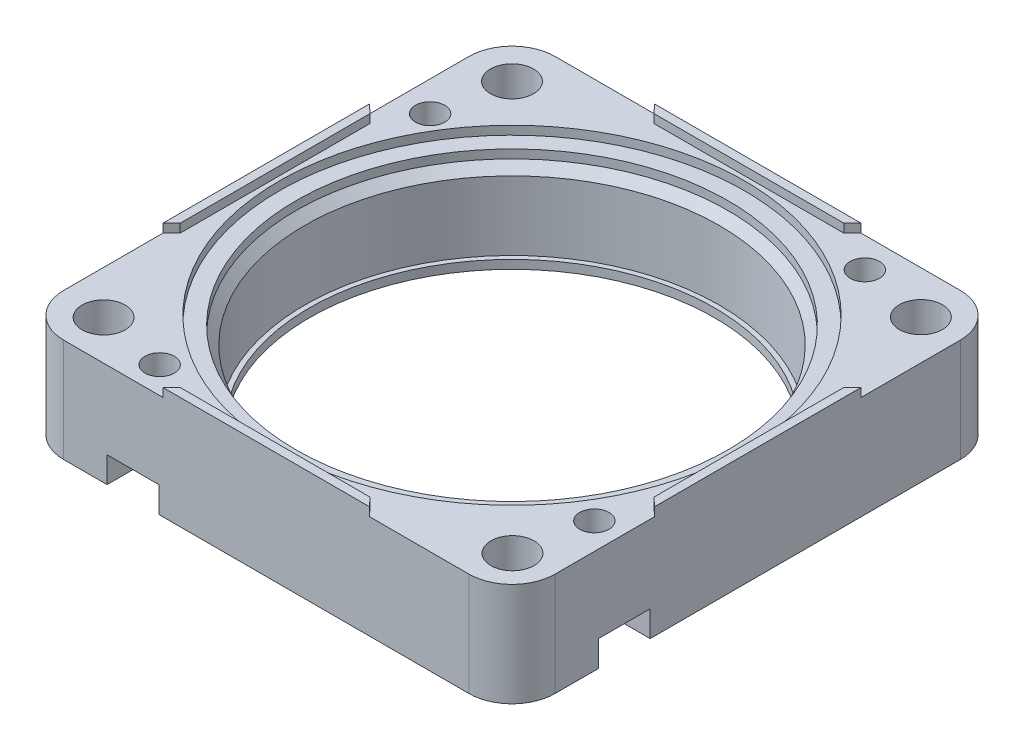
SolidWorks part; units mm, degrees
ref_plane "Front Plane" through (0, 0, 0) normal (0, 0, 1) x (1, 0, 0)
ref_plane "Top Plane" through (0, 0, 0) normal (0, 1, 0) x (1, 0, 0)
ref_plane "Right Plane" through (0, 0, 0) normal (1, 0, 0) x (0, 0, -1)
sketch "Sketch1" plane through (0, 0, 0) normal (0, 1, 0) x (1, 0, 0)
  line L1 (28.5, -28.5) -> (-28.5, -28.5)
  line L2 (28.5, -28.5) -> (28.5, 28.5)
  line L3 (28.5, 28.5) -> (-28.5, 28.5)
  line L4 (-28.5, -28.5) -> (-28.5, 28.5)
  line L5 (28.5, -28.5) -> (-28.5, 28.5) construction
  line L6 (28.5, 28.5) -> (-28.5, -28.5) construction
  point P0 (0, 0)
  dimension "D1" = 57
extrude "Boss-Extrude1" add sketch "Sketch1" along normal blind 12
fillet "Fillet1" radius 5 4 edges at (-28.5, 6, 28.5) (-28.5, 6, -28.5) (28.5, 6, -28.5) (28.5, 6, 28.5)
sketch "Sketch2" plane through (0, 12, 0) normal (0, 1, 0) x (1, 0, 0)
  line L4 (-28.5, 23.5) -> (-28.5, -23.5)
  line L5 (-23.5, -28.5) -> (23.5, -28.5)
  line L6 (28.5, -23.5) -> (28.5, 23.5)
  line L7 (23.5, 28.5) -> (-23.5, 28.5)
  line L8 (-28.5, 23.5) -> (-28.5, -23.5)
  line L9 (-23.5, -28.5) -> (23.5, -28.5)
  line L10 (28.5, -23.5) -> (28.5, 23.5)
  line L11 (23.5, 28.5) -> (-23.5, 28.5)
  circle A0 centre (-23.5, 23.5) radius 2.5
  circle A1 centre (-25, 15.5) radius 1.7
  arc A4 (-28.5, -23.5) -> (-23.5, -28.5) centre (-23.5, -23.5) ccw
  arc A5 (23.5, -28.5) -> (28.5, -23.5) centre (23.5, -23.5) ccw
  arc A6 (28.5, 23.5) -> (23.5, 28.5) centre (23.5, 23.5) ccw
  arc A7 (-23.5, 28.5) -> (-28.5, 23.5) centre (-23.5, 23.5) ccw
  arc A8 (-28.5, -23.5) -> (-23.5, -28.5) centre (-23.5, -23.5) ccw
  arc A9 (23.5, -28.5) -> (28.5, -23.5) centre (23.5, -23.5) ccw
  arc A10 (28.5, 23.5) -> (23.5, 28.5) centre (23.5, 23.5) ccw
  arc A11 (-23.5, 28.5) -> (-28.5, 23.5) centre (-23.5, 23.5) ccw
  dimension "D2" = 5
  dimension "D3" = 3.4
  dimension "D4" = 3.5
  dimension "D5" = 8
  dimension "D1" = 0
extrude "Cut-Extrude1" cut sketch "Sketch2" against normal through all contours A0 | A1
pattern_circular "CirPattern2" count 4 over 360 about axis through (0.2152, 0, 0.1882) along (0, 1, 0) of "Cut-Extrude1"
sketch "Sketch3" plane through (0, 12, 0) normal (0, 1, 0) x (1, 0, 0)
  circle A0 centre (0, 0) radius 27
  dimension "D1" = 54
extrude "Cut-Extrude2" cut sketch "Sketch3" against normal blind 1
sketch "Sketch4" plane through (0, 11, 0) normal (0, 1, 0) x (1, 0, 0)
  circle A0 centre (0, 0) radius 25.05
  dimension "D1" = 50.1
extrude "Cut-Extrude3" cut sketch "Sketch4" against normal blind 2
chamfer "Chamfer1" distance 1 angle 45 1 edges at (0, 9, 25.05)
sketch "Sketch5" plane through (0, 9, 0) normal (0, 1, 0) x (1, 0, 0)
  circle A1 centre (0, 0) radius 24.05
  circle A2 centre (0, 0) radius 24.05
  dimension "D1" = 0
extrude "Cut-Extrude4" cut sketch "Sketch5" against normal blind 8
sketch "Sketch6" plane through (0, 1, 0) normal (0, 1, 0) x (1, 0, 0)
  circle A0 centre (0, 0) radius 23.5
  dimension "D1" = 47
extrude "Cut-Extrude5" cut sketch "Sketch6" against normal blind 2
sketch "Sketch7" plane through (0, 12, 0) normal (0, 1, 0) x (1, 0, 0)
  line L0 (27.5, -11) -> (27.5, 11)
  line L1 (27.5, 11) -> (28.5, 11.9966)
  line L2 (28.5, -23.5) -> (28.5, 23.5) construction
  line L3 (0, 0) -> (33.5599, 0)
  line L4 (27.5, -11) -> (28.5, -11.9966)
  line L5 (28.5, -11.9966) -> (28.5, 11.9966)
  point P12 (27.5, 0)
  line M19 (28.5, -23.5) -> (28.5, 23.5)
  dimension "D1" = 11
  dimension "D2" = 1
  dimension "D3" = 134.902
extrude "Boss-Extrude2" add sketch "Sketch7" along normal blind 1 contours L0 L4 L3 M19 | L0 L3 L1 M19
pattern_circular "CirPattern3" count 4 over 360 about axis through (0, 0, 0) along (0, 1, 0) of "Boss-Extrude2"
sketch "Sketch9" plane through (0, 0, 0) normal (0, -1, 0) x (1, 0, 0)
  line L0 (-12.473, 25.4034) -> (-12.473, 28.5)
  line L1 (-23.5, 28.5) -> (23.5, 28.5) construction
  line L2 (-18.473, 25.4034) -> (-18.473, 28.9104)
  line L3 (-18.473, 28.9104) -> (-12.473, 28.9104)
  line L4 (-12.473, 28.9104) -> (-12.473, 28.4244)
  circle A0 centre (-15.473, 25.4034) radius 1.7 construction
  circle A1 centre (-15.473, 25.4034) radius 1.7
  circle A2 centre (-15.473, 25.4034) radius 3
  circle M9 centre (-15.473, 25.4034) radius 1.7
  line M12 (23.5, 28.5) -> (-23.5, 28.5)
  dimension "D1" = 6
extrude "Cut-Extrude8" cut sketch "Sketch9" against normal blind 3 contours A2 M9 | A2 L0 L2 M12 | A1
pattern_circular "CirPattern6" count 4 over 360 about axis through (0, 0, 0) along (0, 1, 0) of "Cut-Extrude8"
